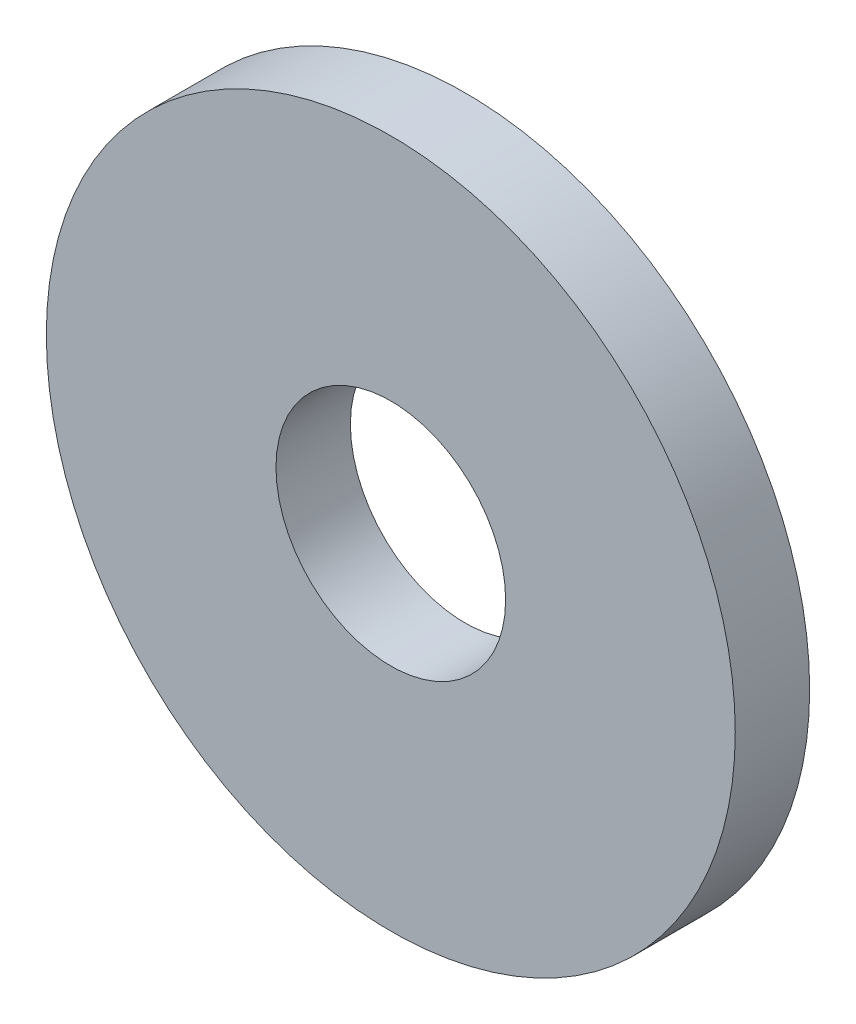
SolidWorks part; units mm, degrees
ref_plane "Front Plane" through (0, 0, 0) normal (0, 0, 1) x (1, 0, 0)
ref_plane "Top Plane" through (0, 0, 0) normal (0, 1, 0) x (1, 0, 0)
ref_plane "Right Plane" through (0, 0, 0) normal (1, 0, 0) x (0, 0, -1)
sketch "Sketch1" plane through (0, 0, 0) normal (0, 0, 1) x (1, 0, 0)
  line L0 (0, 0) -> (0, -1.5875) construction
  circle A0 centre (0, 0) radius 4.7625 construction
  circle A1 centre (0, 0) radius 1.5875 construction
  point P6 (0, -1.5875)
  dimension "OD" = 9.525
  dimension "ID" = 3.175
sketch "Sketch2" plane through (0, 0, 0) normal (1, 0, 0) x (0, 0, -1)
  line L1 (0.5143, -4.7625) -> (-0.5143, -4.7625) construction
  line L2 (0.5143, -4.7625) -> (0.5143, 4.7625) construction
  line L3 (0.5143, 4.7625) -> (-0.5143, 4.7625) construction
  line L4 (-0.5143, -4.7625) -> (-0.5143, 4.7625) construction
  line L5 (0, 4.7625) -> (0, -4.7625) construction
  line L6 (0.5143, 0) -> (-0.5143, 0) construction
  dimension "Thickness" = 1.0287
sketch "Sketch3" plane through (0, 0, 0) normal (0, 0, 1) x (1, 0, 0)
  circle A0 centre (0, 0) radius 4.7625 construction
  circle A1 centre (0, 0) radius 4.7625
  circle A2 centre (0, 0) radius 1.5875 construction
  circle A3 centre (0, 0) radius 1.5875
extrude "Boss-Extrude1" add sketch "Sketch3" along normal mid plane 1.0287
equation "\"D1@Boss-Extrude1\"= \"Thickness@Sketch2\""
